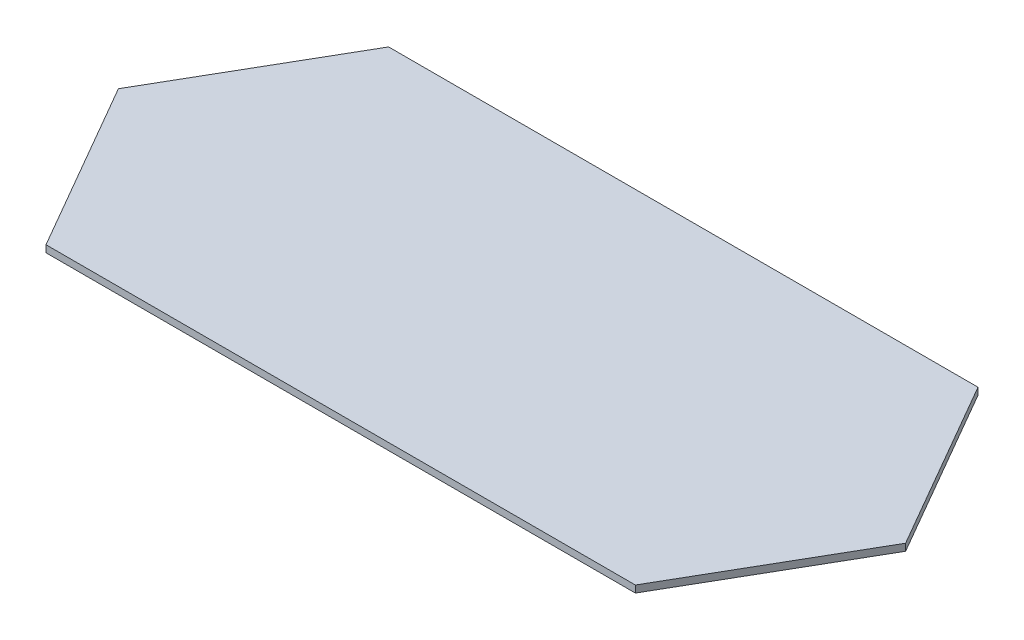
SolidWorks part; units mm, degrees
material "Oak"
ref_plane "Front Plane" through (0, 0, 0) normal (0, 0, 1) x (1, 0, 0)
ref_plane "Top Plane" through (0, 0, 0) normal (0, 1, 0) x (1, 0, 0)
ref_plane "Right Plane" through (0, 0, 0) normal (1, 0, 0) x (0, 0, -1)
sketch "Sketch1" plane through (0, 0, 0) normal (0, 1, 0) x (1, 0, 0)
  line L0 (89.8213, 155.575) -> (265.7787, 155.575)
  line L1 (89.8213, -155.575) -> (179.6425, 0) construction
  line L2 (179.6425, 0) -> (89.8213, 155.575) construction
  line L3 (89.8213, 155.575) -> (-89.8213, 155.575)
  line L4 (-89.8213, 155.575) -> (-179.6425, 0)
  line L5 (-179.6425, 0) -> (-89.8213, -155.575)
  line L6 (-89.8213, -155.575) -> (89.8213, -155.575)
  line L7 (445.4213, -155.575) -> (535.2425, 0)
  line L8 (535.2425, 0) -> (445.4213, 155.575)
  line L9 (445.4213, 155.575) -> (265.7787, 155.575)
  line L10 (265.7787, 155.575) -> (175.9575, 0) construction
  line L11 (175.9575, 0) -> (265.7787, -155.575) construction
  line L12 (265.7787, -155.575) -> (445.4213, -155.575)
  line L13 (265.7787, -155.575) -> (89.8213, -155.575)
  circle A0 centre (0, 0) radius 155.575 construction
  circle A1 centre (355.6, 0) radius 155.575 construction
  dimension "D1" = 355.6
extrude "Boss-Extrude1" add sketch "Sketch1" along normal blind 6.35
